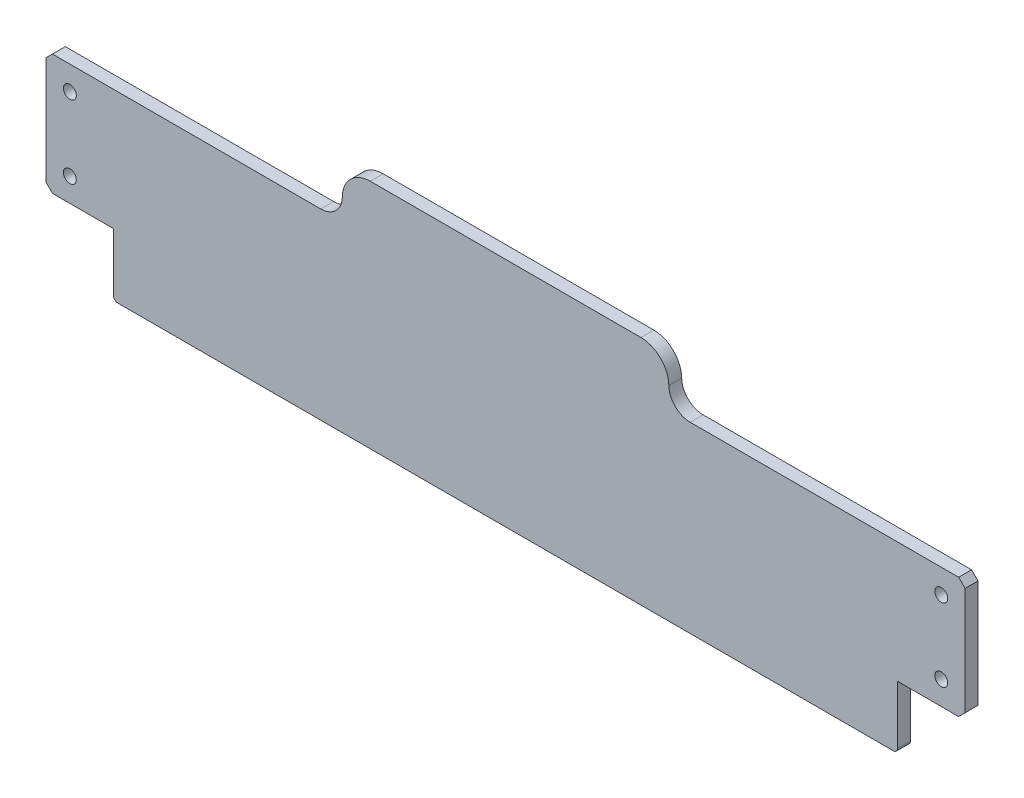
SolidWorks part; units mm, degrees
ref_plane "Plano frontal" through (0, 0, 0) normal (0, 0, 1) x (1, 0, 0)
ref_plane "Plano superior" through (0, 0, 0) normal (0, 1, 0) x (1, 0, 0)
ref_plane "Plano direito" through (0, 0, 0) normal (1, 0, 0) x (0, 0, -1)
sketch "Esboço1" plane through (0, 0, 0) normal (0, 0, 1) x (1, 0, 0)
  line L0 (0, 103.5) -> (0, 180)
  line L1 (0, 0) -> (365, 0)
  line L2 (0, 0) -> (0, 4.5)
  line L3 (0, 180) -> (365, 180)
  line L4 (365, 0) -> (365, 4.5)
  line L5 (0, 103.5) -> (-6, 103.5)
  line L7 (0, 4.5) -> (-6, 4.5)
  line L8 (-6, 103.5) -> (-6, 4.5)
  line L9 (365, 103.5) -> (371, 103.5)
  line L11 (365, 4.5) -> (371, 4.5)
  line L12 (371, 103.5) -> (371, 4.5)
  line L13 (365, 103.5) -> (365, 180)
  dimension "D1" = 365
  dimension "D2" = 180
  dimension "D3" = 6
  dimension "D4" = 6
  dimension "D5" = 99
  dimension "D6" = 99
  dimension "D7" = 4.5
extrude "Ressalto-extrusão1" add sketch "Esboço1" along normal blind 6 contours L3 L13 L9 L12 L11 L4 L1 L2 L7 L8 L5 L0
sketch "Esboço2" plane through (0, 0, 6) normal (0, 0, 1) x (1, 0, 0)
  line L5 (182.5, 180) -> (182.5, 0) construction
  line L6 (18.5737, 163.9646) -> (106.5221, 163.9646)
  line L7 (18.5737, 163.9646) -> (18.5737, 73.1702)
  line L8 (18.5737, 73.1702) -> (106.5221, 73.1702)
  line L9 (106.5221, 163.9646) -> (106.5221, 73.1702)
  line L10 (0, 180) -> (365, 180) construction
  line L11 (0, 0) -> (365, 0) construction
  line L12 (346.4263, 73.1702) -> (258.4779, 73.1702)
  line L13 (258.4779, 163.9646) -> (258.4779, 73.1702)
  line L14 (346.4263, 163.9646) -> (258.4779, 163.9646)
  line L15 (346.4263, 163.9646) -> (346.4263, 73.1702)
extrude "Corte-extrusão1" cut sketch "Esboço2" against normal blind 10
fillet "Filete1" radius 10 8 edges at (346.4263, 73.1702, 3) (258.4779, 73.1702, 3) (346.4263, 163.9646, 3) (258.4779, 163.9646, 3) (106.5221, 73.1702, 3) (18.5737, 73.1702, 3) (106.5221, 163.9646, 3) (18.5737, 163.9646, 3)
fillet "Filete2" radius 1 4 edges at (371, 103.5, 3) (371, 4.5, 3) (-6, 4.5, 3) (-6, 103.5, 3)
sketch "Esboço3" plane through (0, 0, 6) normal (0, 0, 1) x (1, 0, 0)
  line L0 (0, 103.5) -> (0, 180) construction
  line L1 (0, 163.9646) -> (-6, 163.9646)
  line L2 (0, 163.9646) -> (0, 143.9646)
  line L3 (0, 143.9646) -> (-6, 143.9646)
  line L4 (-6, 163.9646) -> (-6, 143.9646)
  line L5 (96.5221, 163.9646) -> (28.5737, 163.9646) construction
  line L6 (182.5, 180) -> (182.5, 0) construction
  line L7 (0, 180) -> (365, 180) construction
  line L8 (0, 0) -> (365, 0) construction
  line L9 (371, 163.9646) -> (371, 143.9646)
  line L10 (365, 143.9646) -> (371, 143.9646)
  line L11 (365, 163.9646) -> (365, 143.9646)
  line L12 (365, 163.9646) -> (371, 163.9646)
  dimension "D1" = 20
  dimension "D2" = 6
extrude "Ressalto-extrusão2" add sketch "Esboço3" against normal blind 6
fillet "Filete3" radius 1 4 edges at (-6, 143.9646, 3) (-6, 163.9646, 3) (371, 143.9646, 3) (371, 163.9646, 3)
sketch "Esboço4" plane through (371, 0, 0) normal (1, 0, 0) x (0, 0, -1)
  line L0 (-6, 103.5) -> (0, 103.5)
  line L1 (-6, 103.5) -> (-6, 93.892)
  line L2 (0, 103.5) -> (0, 93.892)
  line L3 (-6, 93.892) -> (0, 93.892)
extrude "Corte-extrusão2" cut sketch "Esboço4" against normal blind 6
sketch "Esboço5" plane through (0, 0, 6) normal (0, 0, 1) x (1, 0, 0)
  line L15 (183.0364, 46.4519) -> (160.3948, 23.8103)
  line L16 (183.0364, 52.0946) -> (183.0222, 52.1087)
  line L17 (154.7521, 23.8103) -> (154.7379, 23.8244)
  line L18 (177.3795, 52.1087) -> (154.7379, 29.4671)
  line L20 (177.3795, 67.4813) -> (177.3654, 67.4671)
  line L21 (183.0222, 67.4813) -> (205.6638, 44.8397)
  line L22 (177.3654, 61.8244) -> (200.0069, 39.1829)
  line L23 (205.6638, 39.197) -> (205.6496, 39.1829)
  line L24 (183.0364, 84.4519) -> (160.3948, 61.8103)
  line L25 (183.0364, 90.0946) -> (183.0222, 90.1087)
  line L26 (154.7521, 61.8103) -> (154.7379, 61.8244)
  line L27 (177.3795, 90.1087) -> (154.7379, 67.4671)
  line L28 (171.7156, 73.1311) -> (177.3724, 67.4742) construction
  line L29 (177.3795, 105.4813) -> (177.3654, 105.4671)
  line L30 (183.0222, 105.4813) -> (205.6638, 82.8397)
  line L31 (177.3654, 99.8244) -> (200.0069, 77.1829)
  line L32 (205.6638, 77.197) -> (205.6496, 77.1829)
  line L33 (183.0364, 122.4519) -> (160.3948, 99.8103)
  line L34 (183.0364, 128.0946) -> (183.0222, 128.1087)
  line L35 (154.7521, 99.8103) -> (154.7379, 99.8244)
  line L36 (177.3795, 128.1087) -> (154.7379, 105.4671)
  line L37 (171.7156, 111.1311) -> (177.3724, 105.4742) construction
  line L38 (177.3795, 143.4813) -> (177.3654, 143.4671)
  line L39 (183.0222, 143.4813) -> (205.6638, 120.8397)
  line L40 (177.3654, 137.8244) -> (200.0069, 115.1829)
  line L41 (205.6638, 115.197) -> (205.6496, 115.1829)
  line L42 (183.0364, 160.4519) -> (160.3948, 137.8103)
  line L43 (183.0364, 166.0946) -> (183.0222, 166.1087)
  line L44 (154.7521, 137.8103) -> (154.7379, 137.8244)
  line L45 (177.3795, 166.1087) -> (154.7379, 143.4671)
  line L46 (171.7156, 149.1311) -> (177.3724, 143.4742) construction
  arc A12 (183.0364, 52.0946) -> (183.0364, 46.4519) centre (180.215, 49.2732) cw
  arc A13 (177.3795, 52.1087) -> (183.0222, 52.1087) centre (180.2009, 49.2873) cw
  arc A14 (160.3948, 23.8103) -> (154.7521, 23.8103) centre (157.5734, 26.6316) cw
  arc A15 (154.7379, 23.8244) -> (154.7379, 29.4671) centre (157.5593, 26.6458) cw
  arc A16 (205.6638, 44.8397) -> (205.6638, 39.197) centre (202.8424, 42.0184) cw
  arc A17 (205.6496, 39.1829) -> (200.0069, 39.1829) centre (202.8283, 42.0042) cw
  arc A18 (177.3654, 61.8244) -> (177.3654, 67.4671) centre (180.1867, 64.6458) cw
  arc A19 (183.0222, 67.4813) -> (177.3795, 67.4813) centre (180.2009, 64.6599) ccw
  arc A20 (183.0364, 90.0946) -> (183.0364, 84.4519) centre (180.215, 87.2732) cw
  arc A21 (177.3795, 90.1087) -> (183.0222, 90.1087) centre (180.2009, 87.2873) cw
  arc A22 (160.3948, 61.8103) -> (154.7521, 61.8103) centre (157.5734, 64.6316) cw
  arc A23 (154.7379, 61.8244) -> (154.7379, 67.4671) centre (157.5593, 64.6458) cw
  arc A24 (205.6638, 82.8397) -> (205.6638, 77.197) centre (202.8424, 80.0184) cw
  arc A25 (205.6496, 77.1829) -> (200.0069, 77.1829) centre (202.8283, 80.0042) cw
  arc A26 (177.3654, 99.8244) -> (177.3654, 105.4671) centre (180.1867, 102.6458) cw
  arc A27 (183.0222, 105.4813) -> (177.3795, 105.4813) centre (180.2009, 102.6599) ccw
  arc A28 (183.0364, 128.0946) -> (183.0364, 122.4519) centre (180.215, 125.2732) cw
  arc A29 (177.3795, 128.1087) -> (183.0222, 128.1087) centre (180.2009, 125.2873) cw
  arc A30 (160.3948, 99.8103) -> (154.7521, 99.8103) centre (157.5734, 102.6316) cw
  arc A31 (154.7379, 99.8244) -> (154.7379, 105.4671) centre (157.5593, 102.6458) cw
  arc A32 (205.6638, 120.8397) -> (205.6638, 115.197) centre (202.8424, 118.0184) cw
  arc A33 (205.6496, 115.1829) -> (200.0069, 115.1829) centre (202.8283, 118.0042) cw
  arc A34 (177.3654, 137.8244) -> (177.3654, 143.4671) centre (180.1867, 140.6458) cw
  arc A35 (183.0222, 143.4813) -> (177.3795, 143.4813) centre (180.2009, 140.6599) ccw
  arc A36 (183.0364, 166.0946) -> (183.0364, 160.4519) centre (180.215, 163.2732) cw
  arc A37 (177.3795, 166.1087) -> (183.0222, 166.1087) centre (180.2009, 163.2873) cw
  arc A38 (160.3948, 137.8103) -> (154.7521, 137.8103) centre (157.5734, 140.6316) cw
  arc A39 (154.7379, 137.8244) -> (154.7379, 143.4671) centre (157.5593, 140.6458) cw
extrude "Corte-extrusão3" [suppressed] cut sketch "Esboço5" against normal through all
sketch "Esboço6" plane through (0, 0, 6) normal (0, 0, 1) x (1, 0, 0)
  line L0 (106.5221, 118.5674) -> (258.4779, 118.5674)
  line L1 (106.5221, 83.1702) -> (106.5221, 153.9646) construction
  line L2 (258.4779, 153.9646) -> (258.4779, 83.1702) construction
  line L3 (346.4263, 153.9646) -> (346.4263, 180)
  line L4 (0, 180) -> (365, 180) construction
  line L5 (18.5737, 153.9646) -> (18.5737, 180)
  line L6 (18.5737, 180) -> (346.4263, 180)
  line L7 (106.5221, 118.5674) -> (18.5737, 153.9646)
  line L8 (258.4779, 118.5674) -> (346.4263, 153.9646)
extrude "Corte-extrusão4" cut sketch "Esboço6" against normal through all
fillet "Filete4" [suppressed] radius 6
sketch "Esboço7" plane through (0, 0, 6) normal (0, 0, 1) x (1, 0, 0)
  line L0 (-6, 162.9646) -> (-6, 144.9646) construction
  line L1 (-5, 153.9646) -> (-8.7571, 153.9646) construction
  line L2 (180, -184.6369) -> (180, 184.6369) construction
  line L4 (365, 153.9646) -> (368.7571, 153.9646) construction
  arc A0 (-5, 163.9646) -> (-5, 143.9646) centre (-5, 153.9646) ccw
  arc A1 (-6, 144.9646) -> (-5, 143.9646) centre (-5, 144.9646) ccw construction
  arc A2 (-5, 163.9646) -> (-5, 143.9646) centre (-35.9885, 153.9646) cw
  circle A3 centre (-9, 153.9646) radius 2.75
  circle A4 centre (369, 153.9646) radius 2.75
  arc A5 (365, 163.9646) -> (365, 143.9646) centre (395.9885, 153.9646) ccw
  arc A6 (365, 163.9646) -> (365, 143.9646) centre (365, 153.9646) cw
  point P16 (180, 0)
  dimension "D2" = 5.5
  dimension "D1" = 3
extrude "Ressalto-extrusão3" add sketch "Esboço7" against normal through all
fillet "Filete5" radius 1 2 edges at (365, 180, 3) (0, 180, 3)
fillet "Filete6" radius 10 2 edges at (258.4779, 118.5674, 3) (106.5221, 118.5674, 3)
sketch "Esboço9" plane through (0, 0, 6) normal (0, 0, 1) x (1, 0, 0)
  line L1 (28.5737, 73.1702) -> (-36.4401, 73.1702)
  line L2 (28.5737, 73.1702) -> (28.5737, 191.4957)
  line L3 (28.5737, 191.4957) -> (-36.4401, 191.4957)
  line L4 (-36.4401, 73.1702) -> (-36.4401, 191.4957)
  line L5 (336.4263, 73.1702) -> (398.5415, 73.1702)
  line L6 (336.4263, 73.1702) -> (336.4263, 204.5241)
  line L7 (336.4263, 204.5241) -> (398.5415, 204.5241)
  line L8 (398.5415, 73.1702) -> (398.5415, 204.5241)
extrude "Corte-extrusão5" cut sketch "Esboço9" against normal through all
sketch "Esboço10" plane through (0, 0, 6) normal (0, 0, 1) x (1, 0, 0)
  line L0 (-6, 73.1702) -> (-6, 5.5) construction
  line L1 (0, 0) -> (-6, 0)
  line L2 (0, 0) -> (0, 17)
  line L3 (0, 17) -> (-6, 17)
  line L4 (-6, 0) -> (-6, 17)
  line L5 (371, 73.1702) -> (371, 5.5) construction
  line L6 (365, 0) -> (371, 0)
  line L7 (365, 0) -> (365, 17)
  line L8 (365, 17) -> (371, 17)
  line L9 (371, 0) -> (371, 17)
  dimension "D1" = 17
  dimension "D2" = 17
extrude "Corte-extrusão6" cut sketch "Esboço10" against normal through all
sketch "Esboço11" plane through (0, 0, 6) normal (0, 0, 1) x (1, 0, 0)
  line L1 (0, 0) -> (365, 0)
  line L2 (0, 0) -> (0, -12)
  line L3 (0, -12) -> (365, -12)
  line L4 (365, 0) -> (365, -12)
  point P5 (365, 0)
  dimension "D1" = 12
extrude "Ressalto-extrusão4" add sketch "Esboço11" against normal through all
sketch "Esboço12" plane through (0, 0, 6) normal (0, 0, 1) x (1, 0, 0)
  line L0 (268.4779, 73.1702) -> (371, 73.1702) construction
  line L1 (371, 17) -> (396.4, 17)
  line L2 (371, 17) -> (371, 73.1702)
  line L3 (371, 73.1702) -> (396.4, 73.1702)
  line L4 (396.4, 17) -> (396.4, 73.1702)
  line L5 (371, 73.1702) -> (371, 17) construction
  line L6 (182.5, 118.5674) -> (182.5, -12) construction
  line L7 (116.5221, 118.5674) -> (248.4779, 118.5674) construction
  line L9 (-31.4, 17) -> (-31.4, 73.1702)
  line L10 (-6, 73.1702) -> (-31.4, 73.1702)
  line L11 (-6, 17) -> (-6, 73.1702)
  line L12 (-6, 17) -> (-31.4, 17)
  line L13 (0, -12) -> (365, -12) construction
  point P14 (182.5, -12)
  dimension "D1" = 25.4
extrude "Ressalto-extrusão5" add sketch "Esboço12" against normal through all
chamfer "Chanfro1" distance 3 angle 45 4 edges at (-31.4, 73.1702, 3) (-31.4, 17, 3) (396.4, 17, 3) (396.4, 73.1702, 3)
fillet "Filete7" radius 2 2 edges at (0, -12, 3) (365, -12, 3)
sketch "Esboço13" plane through (0, 0, 6) normal (0, 0, 1) x (1, 0, 0)
  line L0 (182.5, 118.5674) -> (182.5, -12) construction
  line L1 (116.5221, 118.5674) -> (248.4779, 118.5674) construction
  line L2 (2, -12) -> (363, -12) construction
  circle A0 centre (-20.3, 62) radius 3
  circle A1 centre (-20.3, 28) radius 3
  circle A2 centre (385.3, 28) radius 3
  circle A3 centre (385.3, 62) radius 3
extrude "Corte-extrusão7" cut sketch "Esboço13" against normal through all
sketch "Esboço14" plane through (0, 0, 6) normal (0, 0, 1) x (1, 0, 0)
  line L0 (106.5221, 83.1702) -> (106.5221, 108.5674) construction
  line L1 (106.5221, 95.8688) -> (260.871, 95.8688)
  line L2 (106.5221, 95.8688) -> (106.5221, 131.8853)
  line L3 (106.5221, 131.8853) -> (260.871, 131.8853)
  line L4 (260.871, 95.8688) -> (260.871, 131.8853)
extrude "Corte-extrusão8" cut sketch "Esboço14" against normal through all
fillet "Filete8" radius 13 2 edges at (106.5221, 95.8688, 3) (258.4779, 95.8688, 3)
